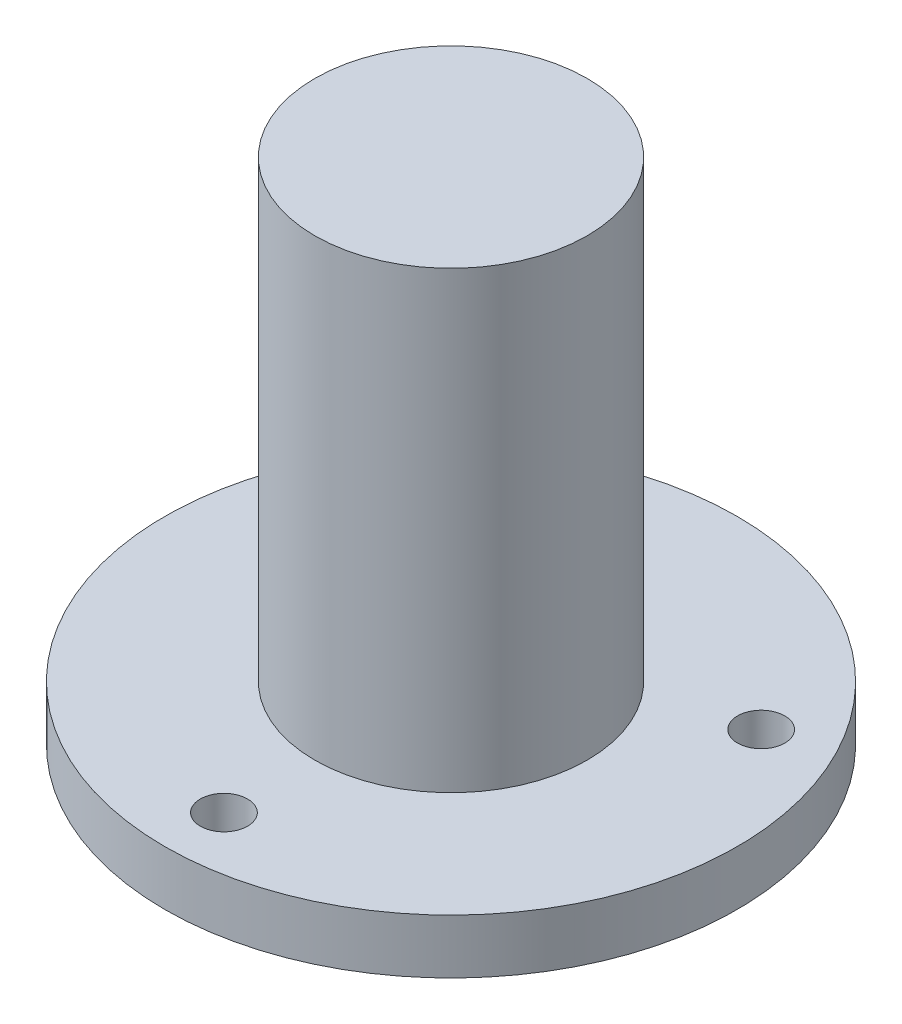
SolidWorks part; units mm, degrees
ref_plane "前视基准面" through (0, 0, 0) normal (0, 0, 1) x (1, 0, 0)
ref_plane "上视基准面" through (0, 0, 0) normal (0, 1, 0) x (1, 0, 0)
ref_plane "右视基准面" through (0, 0, 0) normal (1, 0, 0) x (0, 0, -1)
sketch "草图1" plane through (0, 0, 0) normal (0, 1, 0) x (1, 0, 0)
  circle A0 centre (0, 0) radius 31.5
  dimension "D1" = 63
extrude "凸台-拉伸1" add sketch "草图1" along normal blind 6
sketch "草图2" plane through (0, 6, 0) normal (0, 1, 0) x (1, 0, 0)
  circle A0 centre (0, 0) radius 15
  dimension "D1" = 30
extrude "凸台-拉伸2" add sketch "草图2" along normal blind 50
sketch "草图3" plane through (0, 0, 0) normal (0, -1, 0) x (1, 0, 0)
  line L0 (0, 0) -> (0, 25) construction
  line L1 (0, 0) -> (-21.6506, -12.5) construction
  line L2 (0, 0) -> (21.6506, -12.5) construction
  circle A0 centre (0, 0) radius 25 construction
  circle A1 centre (-21.6506, -12.5) radius 2.6
  circle A2 centre (0, 25) radius 2.6
  circle A3 centre (21.6506, -12.5) radius 2.6
  dimension "D1" = 50
  dimension "D4" = 5.2
  dimension "D5" = 5.2
  dimension "D6" = 5.2
  dimension "D2" = 120
  dimension "D3" = 120
extrude "切除-拉伸1" cut sketch "草图3" against normal through all
